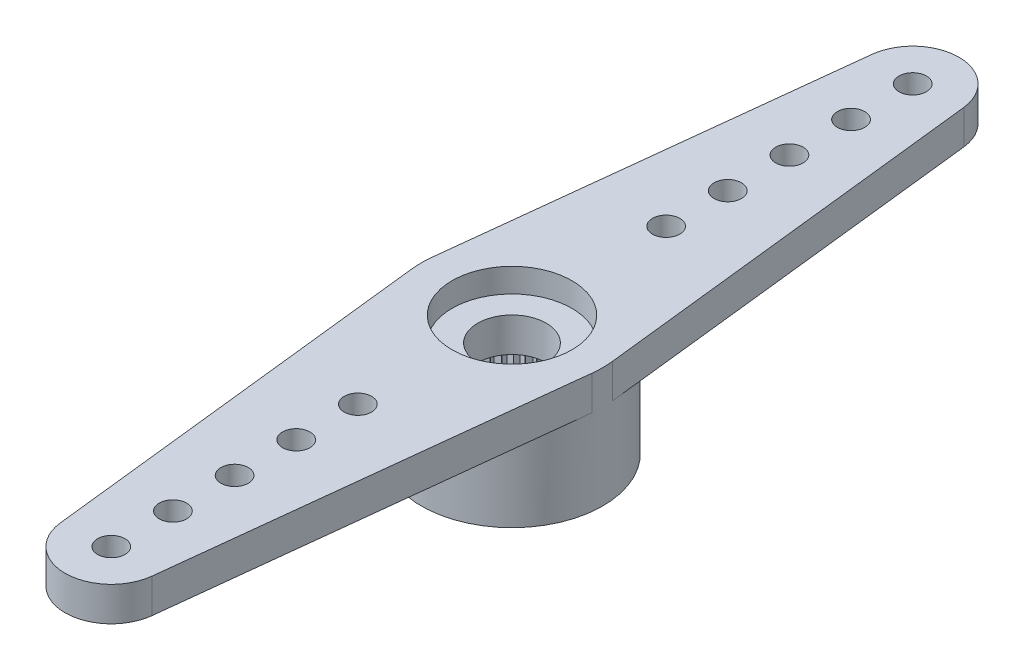
SolidWorks part; units mm, degrees
ref_plane "Front Plane" through (0, 0, 0) normal (0, 0, 1) x (1, 0, 0)
ref_plane "Top Plane" through (0, 0, 0) normal (0, 1, 0) x (1, 0, 0)
ref_plane "Right Plane" through (0, 0, 0) normal (1, 0, 0) x (0, 0, -1)
sketch "Sketch1" plane through (0, 0, 0) normal (0, 1, 0) x (1, 0, 0)
  line L0 (0, 0) -> (0, -14.859) construction
  line L1 (-1.7039, -15.0495) -> (-3.3447, -0.3739)
  line L2 (1.7039, -15.0495) -> (3.3447, -0.3739)
  line L3 (-10.3709, 0) -> (9.7084, 0) construction
  line L4 (1.7039, 15.0495) -> (3.3447, 0.3739)
  line L5 (-1.7039, 15.0495) -> (-3.3447, 0.3739)
  arc A0 (3.3447, -0.3739) -> (3.3447, 0.3739) centre (0, 0) ccw
  arc A1 (-1.7039, -15.0495) -> (1.7039, -15.0495) centre (0, -14.859) ccw
  arc A2 (-1.7039, 15.0495) -> (1.7039, 15.0495) centre (0, 14.859) cw
  arc A3 (-3.3447, 0.3739) -> (-3.3447, -0.3739) centre (0, 0) ccw
  dimension "D1" = 6.731
  dimension "D2" = 3.429
  dimension "D3" = 19.939
extrude "Boss-Extrude1" add sketch "Sketch1" along normal blind 1.27
sketch "Sketch2" plane through (0, 0, 0) normal (0, -1, 0) x (1, 0, 0)
  circle A0 centre (0, 0) radius 3.3655
extrude "Boss-Extrude2" add sketch "Sketch2" along normal blind 3.175
sketch "Sketch3" plane through (0, -3.175, 0) normal (0, -1, 0) x (-1, 0, 0)
  line L0 (0.3447, 2.4524) -> (0.1605, 2.2167)
  line L1 (0, 2.4765) -> (-0.1496, 2.2175)
  line L2 (0.4567, 2.1751) -> (0.3447, 2.4524)
  line L3 (0.1496, 2.2175) -> (0, 2.4765)
  line L4 (0.6826, 2.3806) -> (0.4675, 2.1728)
  line L5 (0.755, 2.0903) -> (0.6826, 2.3806)
  line L6 (1.0073, 2.2624) -> (0.7653, 2.0866)
  line L7 (1.0385, 1.9649) -> (1.0073, 2.2624)
  line L8 (1.3123, 2.1002) -> (1.0482, 1.9598)
  line L9 (1.3019, 1.8013) -> (1.3123, 2.1002)
  line L10 (1.5919, 1.8971) -> (1.3108, 1.7948)
  line L11 (1.5399, 1.6025) -> (1.5919, 1.8971)
  line L12 (1.8404, 1.6571) -> (1.5478, 1.5949)
  line L13 (1.748, 1.3726) -> (1.8404, 1.6571)
  line L14 (2.0531, 1.3848) -> (1.7547, 1.364)
  line L15 (1.922, 1.116) -> (2.0531, 1.3848)
  line L16 (2.2259, 1.0856) -> (1.9275, 1.1065)
  line L17 (2.0586, 0.8377) -> (2.2259, 1.0856)
  line L18 (2.3553, 0.7653) -> (2.0627, 0.8275)
  line L19 (2.1551, 0.543) -> (2.3553, 0.7653)
  line L20 (2.4389, 0.43) -> (2.1578, 0.5323)
  line L21 (2.2097, 0.2378) -> (2.4389, 0.43)
  line L22 (2.475, 0.0864) -> (2.2109, 0.2269)
  line L23 (2.2213, -0.0721) -> (2.475, 0.0864)
  line L24 (2.4629, -0.2589) -> (2.2209, -0.0831)
  line L25 (2.1897, -0.3805) -> (2.4629, -0.2589)
  line L26 (2.4029, -0.5991) -> (2.1878, -0.3913)
  line L27 (2.1154, -0.6816) -> (2.4029, -0.5991)
  line L28 (2.2962, -0.9277) -> (2.112, -0.692)
  line L29 (2, -0.9693) -> (2.2962, -0.9277)
  line L30 (2.1447, -1.2383) -> (1.9952, -0.9792)
  line L31 (1.8456, -1.2382) -> (2.1447, -1.2383)
  line L32 (1.9515, -1.5247) -> (1.8395, -1.2474)
  line L33 (1.6553, -1.4831) -> (1.9515, -1.5247)
  line L34 (1.7203, -1.7814) -> (1.648, -1.4912)
  line L35 (1.4328, -1.699) -> (1.7203, -1.7814)
  line L36 (1.4557, -2.0035) -> (1.4244, -1.7061)
  line L37 (1.1824, -1.8819) -> (1.4557, -2.0035)
  line L38 (1.1626, -2.1866) -> (1.1731, -1.8877)
  line L39 (0.909, -2.0281) -> (1.1626, -2.1866)
  line L40 (0.847, -2.3271) -> (0.899, -2.0326)
  line L41 (0.6179, -2.1349) -> (0.847, -2.3271)
  line L42 (0.5149, -2.4224) -> (0.6073, -2.1379)
  line L43 (0.3147, -2.2001) -> (0.5149, -2.4224)
  line L44 (0.1728, -2.4705) -> (0.3039, -2.2016)
  line L45 (-0.22, 2.0955) -> (0, 2.0955) [skipped]
  line L46 (0.0055, -2.2225) -> (0.1728, -2.4705)
  line L47 (-0.1728, -2.4705) -> (-0.0055, -2.2225)
  line L48 (-0.3039, -2.2016) -> (-0.1728, -2.4705)
  line L49 (-0.5149, -2.4224) -> (-0.3147, -2.2001)
  line L50 (-0.6073, -2.1379) -> (-0.5149, -2.4224)
  line L51 (-0.847, -2.3271) -> (-0.6179, -2.1349)
  line L52 (-0.899, -2.0326) -> (-0.847, -2.3271)
  line L53 (-1.1626, -2.1866) -> (-0.909, -2.0281)
  line L54 (-1.1731, -1.8877) -> (-1.1626, -2.1866)
  line L55 (-1.4557, -2.0035) -> (-1.1824, -1.8819)
  line L56 (-1.4244, -1.7061) -> (-1.4557, -2.0035)
  line L57 (-1.7203, -1.7814) -> (-1.4328, -1.699)
  line L58 (-1.648, -1.4912) -> (-1.7203, -1.7814)
  line L59 (-1.9515, -1.5247) -> (-1.6553, -1.4831)
  line L60 (-1.8395, -1.2474) -> (-1.9515, -1.5247)
  line L61 (-2.1447, -1.2382) -> (-1.8456, -1.2383)
  line L62 (-1.9952, -0.9792) -> (-2.1447, -1.2382)
  line L63 (-2.2962, -0.9277) -> (-2, -0.9693)
  line L64 (-2.112, -0.692) -> (-2.2962, -0.9277)
  line L65 (-2.4029, -0.5991) -> (-2.1154, -0.6816)
  line L66 (-2.1878, -0.3913) -> (-2.4029, -0.5991)
  line L67 (-2.4629, -0.2589) -> (-2.1897, -0.3805)
  line L68 (-2.2209, -0.0831) -> (-2.4629, -0.2589)
  line L69 (-2.475, 0.0864) -> (-2.2213, -0.0721)
  line L70 (-2.2109, 0.2269) -> (-2.475, 0.0864)
  line L71 (-2.4389, 0.43) -> (-2.2097, 0.2378)
  line L72 (-2.1578, 0.5323) -> (-2.4389, 0.43)
  line L73 (-2.3553, 0.7653) -> (-2.1551, 0.543)
  line L74 (-2.0627, 0.8275) -> (-2.3553, 0.7653)
  line L75 (-2.2259, 1.0856) -> (-2.0586, 0.8377)
  line L76 (-1.9275, 1.1065) -> (-2.2259, 1.0856)
  line L77 (-2.0531, 1.3848) -> (-1.922, 1.116)
  line L78 (-1.7547, 1.364) -> (-2.0531, 1.3848)
  line L79 (-1.8404, 1.6571) -> (-1.748, 1.3726)
  line L80 (-1.5478, 1.5949) -> (-1.8404, 1.6571)
  line L81 (-1.5919, 1.8971) -> (-1.5399, 1.6025)
  line L82 (-1.3108, 1.7948) -> (-1.5919, 1.8971)
  line L83 (-1.3123, 2.1002) -> (-1.3019, 1.8013)
  line L84 (-1.0482, 1.9598) -> (-1.3123, 2.1002)
  line L85 (-1.0073, 2.2624) -> (-1.0385, 1.9649)
  line L86 (-0.7653, 2.0866) -> (-1.0073, 2.2624)
  line L87 (-0.6826, 2.3806) -> (-0.755, 2.0903)
  line L88 (-0.4675, 2.1728) -> (-0.6826, 2.3806)
  line L89 (-0.3447, 2.4524) -> (-0.4567, 2.1751)
  line L90 (-0.1605, 2.2167) -> (-0.3447, 2.4524)
  arc A0 (-0.1496, 2.2175) -> (-0.1605, 2.2167) centre (0, 0) ccw
  circle A1 centre (0, 2.2225) radius 0.127 construction
  arc A2 (0.1605, 2.2167) -> (0.1496, 2.2175) centre (0, 0) ccw
  arc A3 (0.4675, 2.1728) -> (0.4567, 2.1751) centre (0, 0) ccw
  arc A4 (0.7653, 2.0866) -> (0.755, 2.0903) centre (0, 0) ccw
  arc A5 (1.0482, 1.9598) -> (1.0385, 1.9649) centre (0, 0) ccw
  arc A6 (1.3108, 1.7948) -> (1.3019, 1.8013) centre (0, 0) ccw
  arc A7 (1.5478, 1.5949) -> (1.5399, 1.6025) centre (0, 0) ccw
  arc A8 (1.7547, 1.364) -> (1.748, 1.3726) centre (0, 0) ccw
  arc A9 (1.9275, 1.1065) -> (1.922, 1.116) centre (0, 0) ccw
  arc A10 (-0.4567, 2.1751) -> (-0.4675, 2.1728) centre (0, 0) ccw
  arc A11 (-0.755, 2.0903) -> (-0.7653, 2.0866) centre (0, 0) ccw
  arc A12 (-1.0385, 1.9649) -> (-1.0482, 1.9598) centre (0, 0) ccw
  arc A13 (-1.3019, 1.8013) -> (-1.3108, 1.7948) centre (0, 0) ccw
  arc A14 (-1.5399, 1.6025) -> (-1.5478, 1.5949) centre (0, 0) ccw
  arc A15 (-1.748, 1.3726) -> (-1.7547, 1.364) centre (0, 0) ccw
  arc A16 (-1.922, 1.116) -> (-1.9275, 1.1065) centre (0, 0) ccw
  arc A17 (-2.0586, 0.8377) -> (-2.0627, 0.8275) centre (0, 0) ccw
  arc A18 (-2.1551, 0.543) -> (-2.1578, 0.5323) centre (0, 0) ccw
  arc A19 (-2.2097, 0.2378) -> (-2.2109, 0.2269) centre (0, 0) ccw
  arc A20 (-2.2213, -0.0721) -> (-2.2209, -0.0831) centre (0, 0) ccw
  arc A21 (2.0627, 0.8275) -> (2.0586, 0.8377) centre (0, 0) ccw
  arc A22 (2.1578, 0.5323) -> (2.1551, 0.543) centre (0, 0) ccw
  arc A23 (2.2109, 0.2269) -> (2.2097, 0.2378) centre (0, 0) ccw
  arc A24 (2.2209, -0.0831) -> (2.2213, -0.0721) centre (0, 0) ccw
  arc A25 (2.1878, -0.3913) -> (2.1897, -0.3805) centre (0, 0) ccw
  arc A26 (2.112, -0.692) -> (2.1154, -0.6816) centre (0, 0) ccw
  arc A27 (1.9952, -0.9792) -> (2, -0.9693) centre (0, 0) ccw
  arc A28 (1.8395, -1.2474) -> (1.8456, -1.2382) centre (0, 0) ccw
  arc A29 (1.648, -1.4912) -> (1.6553, -1.4831) centre (0, 0) ccw
  arc A30 (1.4244, -1.7061) -> (1.4328, -1.699) centre (0, 0) ccw
  arc A31 (1.1731, -1.8877) -> (1.1824, -1.8819) centre (0, 0) ccw
  arc A32 (0.899, -2.0326) -> (0.909, -2.0281) centre (0, 0) ccw
  arc A33 (0.6073, -2.1379) -> (0.6179, -2.1349) centre (0, 0) ccw
  arc A34 (0.3039, -2.2016) -> (0.3147, -2.2001) centre (0, 0) ccw
  arc A35 (-0.0055, -2.2225) -> (0.0055, -2.2225) centre (0, 0) ccw
  arc A36 (-0.3147, -2.2001) -> (-0.3039, -2.2016) centre (0, 0) ccw
  arc A37 (-0.6179, -2.1349) -> (-0.6073, -2.1379) centre (0, 0) ccw
  arc A38 (-0.909, -2.0281) -> (-0.899, -2.0326) centre (0, 0) ccw
  arc A39 (-1.1824, -1.8819) -> (-1.1731, -1.8877) centre (0, 0) ccw
  arc A40 (-1.4328, -1.699) -> (-1.4244, -1.7061) centre (0, 0) ccw
  arc A41 (-1.6553, -1.4831) -> (-1.648, -1.4912) centre (0, 0) ccw
  arc A42 (-1.8456, -1.2383) -> (-1.8395, -1.2474) centre (0, 0) ccw
  arc A43 (-2, -0.9693) -> (-1.9952, -0.9792) centre (0, 0) ccw
  arc A44 (-2.1154, -0.6816) -> (-2.112, -0.692) centre (0, 0) ccw
  arc A45 (-2.1897, -0.3805) -> (-2.1878, -0.3913) centre (0, 0) ccw
  point P145 (0, 0)
  dimension "D1" = 4.445
  dimension "D2" = 0.254
  dimension "D3" = 45
extrude "Cut-Extrude1" cut sketch "Sketch3" against normal blind 2.286
sketch "Sketch4" plane through (0, 1.27, 0) normal (0, 1, 0) x (1, 0, 0)
  circle A0 centre (0, 0) radius 2.2225
  dimension "D1" = 4.445
extrude "Cut-Extrude2" cut sketch "Sketch4" against normal blind 0.889
sketch "Sketch5" plane through (0, 0.381, 0) normal (0, 1, 0) x (1, 0, 0)
  circle A0 centre (0, 0) radius 1.27
  dimension "D1" = 2.54
extrude "Cut-Extrude3" cut sketch "Sketch5" against normal up to next
sketch "Sketch6" plane through (0, 1.27, 0) normal (0, 1, 0) x (1, 0, 0)
  line L0 (0, 0) -> (0, -14.859) construction
  line L1 (-9.0823, 0) -> (8.6618, 0) construction
  circle A0 centre (0, -14.859) radius 0.508
  circle A1 centre (0, -12.573) radius 0.508
  circle A2 centre (0, -10.287) radius 0.508
  circle A3 centre (0, -8.001) radius 0.508
  circle A4 centre (0, -5.715) radius 0.508
  circle A5 centre (0, 5.715) radius 0.508
  circle A6 centre (0, 8.001) radius 0.508
  circle A7 centre (0, 10.287) radius 0.508
  circle A8 centre (0, 12.573) radius 0.508
  circle A9 centre (0, 14.859) radius 0.508
  dimension "D1" = 1.016
  dimension "D2" = 1.016
  dimension "D3" = 1.27
  dimension "D4" = 1.27
  dimension "D5" = 1.27
  dimension "D6" = 1.27
extrude "Cut-Extrude4" cut sketch "Sketch6" against normal up to next
